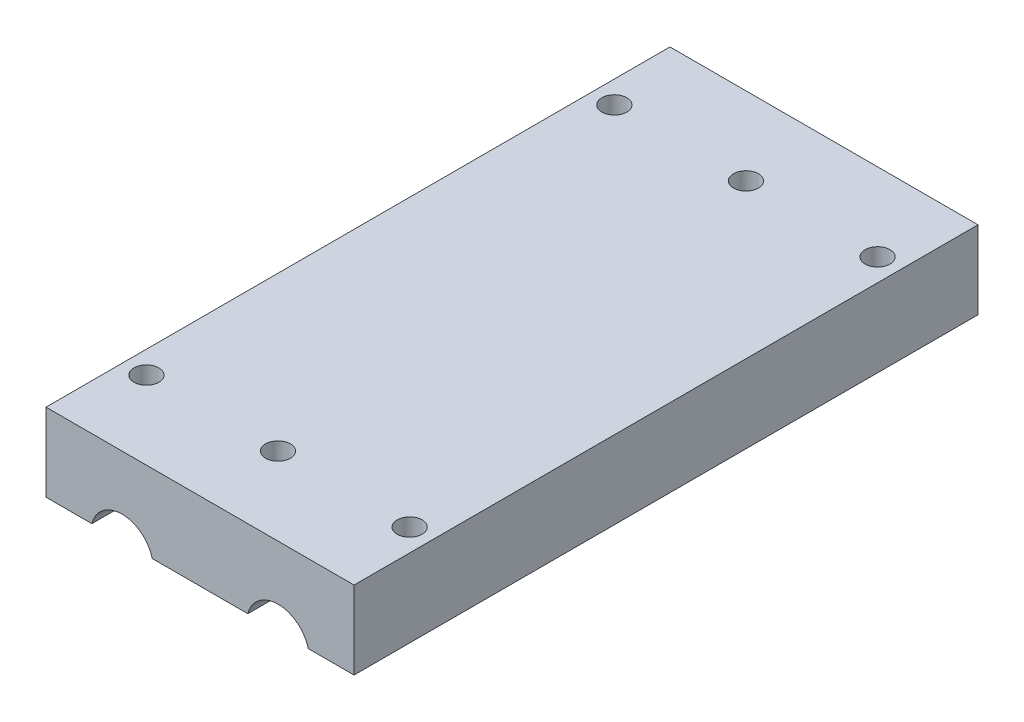
SolidWorks part; units mm, degrees
ref_plane "Alzado" through (0, 0, 0) normal (0, 0, 1) x (1, 0, 0)
ref_plane "Planta" through (0, 0, 0) normal (0, 1, 0) x (1, 0, 0)
ref_plane "Vista lateral" through (0, 0, 0) normal (1, 0, 0) x (0, 0, -1)
sketch "Croquis1" plane through (0, 0, 0) normal (0, 1, 0) x (1, 0, 0)
  line L1 (-19.75, -40) -> (19.75, -40)
  line L2 (-19.75, -40) -> (-19.75, 40)
  line L3 (-19.75, 40) -> (19.75, 40)
  line L4 (19.75, -40) -> (19.75, 40)
  line L5 (-19.75, -40) -> (19.75, 40) construction
  line L6 (-19.75, 40) -> (19.75, -40) construction
  point P0 (0, 0)
extrude "Saliente-Extruir1" add sketch "Croquis1" along normal blind 10
sketch "Croquis2" plane through (0, 0, 40) normal (0, 0, 1) x (1, 0, 0)
  line L0 (0, 0) -> (10, 0) construction
  line L1 (-19.75, 0) -> (19.75, 0) construction
  line L2 (0, 0) -> (-10, 0) construction
  line L3 (0, 0) -> (0, -1) construction
  circle A0 centre (-10, -1) radius 4
  circle A1 centre (10, -1) radius 4
extrude "Cortar-Extruir1" cut sketch "Croquis2" against normal blind 82
sketch "Croquis3" plane through (0, 10, 0) normal (0, 1, 0) x (1, 0, 0)
  line L0 (0, -40) -> (0, 40) construction
  line L1 (-19.75, -40) -> (19.75, -40) construction
  line L2 (19.75, 40) -> (-19.75, 40) construction
  line L3 (-19.75, 0) -> (19.75, 0) construction
  line L4 (-19.75, 40) -> (-19.75, -40) construction
  line L5 (16.875, 0) -> (16.875, -40) construction
  line L6 (-19.75, -30) -> (-16.875, -30) construction
  line L7 (19.75, -40) -> (19.75, 40) construction
  line L8 (-16.875, 0) -> (-16.875, 40) construction
  line L10 (19.75, -30) -> (16.875, -30) construction
  line L11 (-16.875, 0) -> (-16.875, -40) construction
  line L12 (16.875, 0) -> (16.875, 40) construction
  line L13 (-16.875, -30) -> (0, -30) construction
  line L14 (0, -30) -> (16.875, -30) construction
  line L15 (-19.75, 30) -> (-16.875, 30) construction
  line L16 (-16.875, 30) -> (0, 30) construction
  line L17 (0, 30) -> (16.875, 30) construction
  line L18 (16.875, 30) -> (19.75, 30) construction
  circle A0 centre (-16.875, 30) radius 1.6
  circle A1 centre (0, 30) radius 1.6
  circle A2 centre (16.875, 30) radius 1.6
  circle A3 centre (-16.875, -30) radius 1.6
  circle A4 centre (0, -30) radius 1.6
  circle A5 centre (16.875, -30) radius 1.6
extrude "Cortar-Extruir2" cut sketch "Croquis3" against normal blind 11
